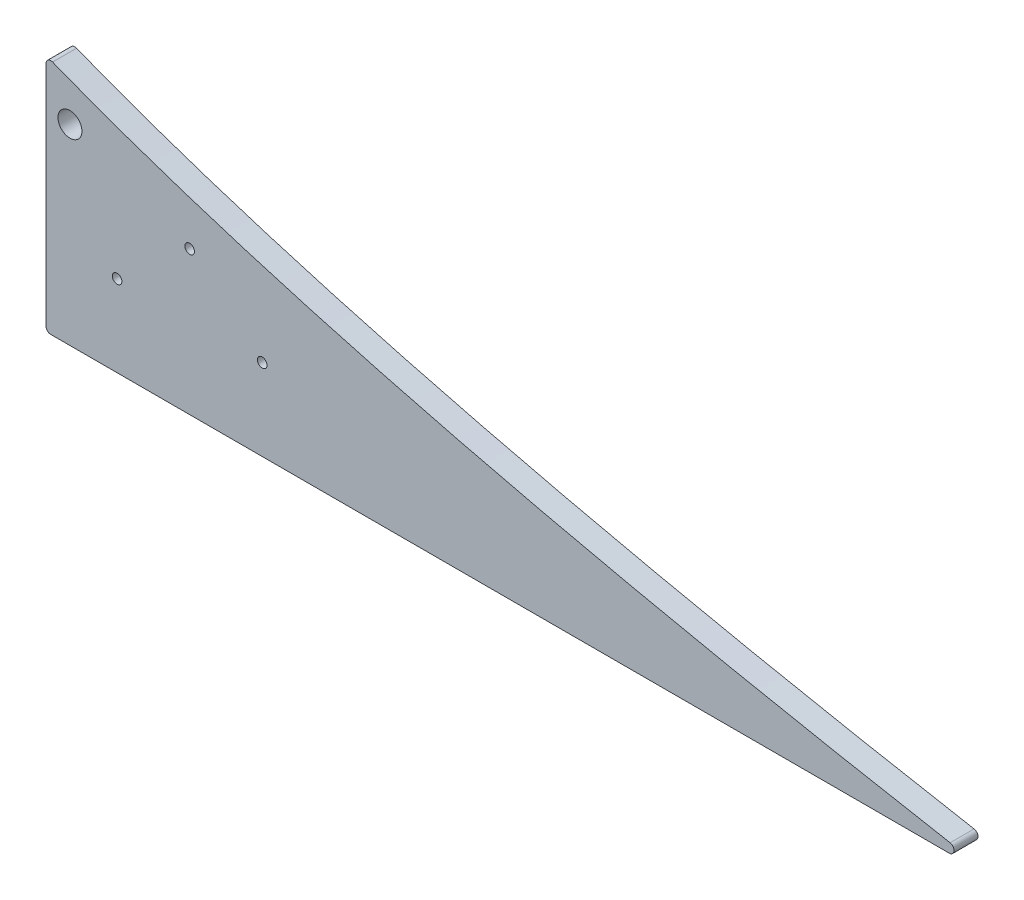
SolidWorks part; units mm, degrees
ref_plane "Front Plane" through (0, 0, 0) normal (0, 0, 1) x (1, 0, 0)
ref_plane "Top Plane" through (0, 0, 0) normal (0, 1, 0) x (1, 0, 0)
ref_plane "Right Plane" through (0, 0, 0) normal (1, 0, 0) x (0, 0, -1)
sketch "Sketch1" plane through (0, 0, 0) normal (0, 0, 1) x (1, 0, 0)
  line L0 (0, 0) -> (0, 127)
  line L3 (508, 0) -> (0, 0)
  circle A0 centre (12.7, 101.6) radius 6.35
  spline S0 degree 2 poles (0, 127) (169.847, 59.0807) (508, 0) knots 0 0 0 1 1 1
  dimension "D3" = 12.7
  dimension "D1" = 127
  dimension "D2" = 508
  dimension "D4" = 12.7
  dimension "D5" = 25.4
extrude "Boss-Extrude1" add sketch "Sketch1" along normal blind 12.7
fillet "Fillet1" radius 2.54 1 edges at (0, 127, 6.35)
fillet "Fillet2" radius 2.54 2 edges at (0, 0, 6.35) (508, 0, 6.35)
sketch "Sketch2" plane through (0, 0, 12.7) normal (0, 0, 1) x (1, 0, 0)
  line L0 (0, 123.2566) -> (0, 2.54) construction
  line L1 (2.54, 0) -> (479.0999, 0) construction
  circle A0 centre (76.2, 76.2) radius 2.54
  circle A1 centre (37.7088, 43.2003) radius 2.54
  circle A2 centre (114.6912, 43.2003) radius 2.54
  dimension "D1" = 5.08
  dimension "D2" = 5.08
  dimension "D3" = 5.08
  dimension "D4" = 38.4912
  dimension "D5" = 32.9997
  dimension "D6" = 38.4912
  dimension "D7" = 32.9997
  dimension "D8" = 76.2
  dimension "D9" = 76.2
extrude "Cut-Extrude1" cut sketch "Sketch2" against normal blind 203.2
